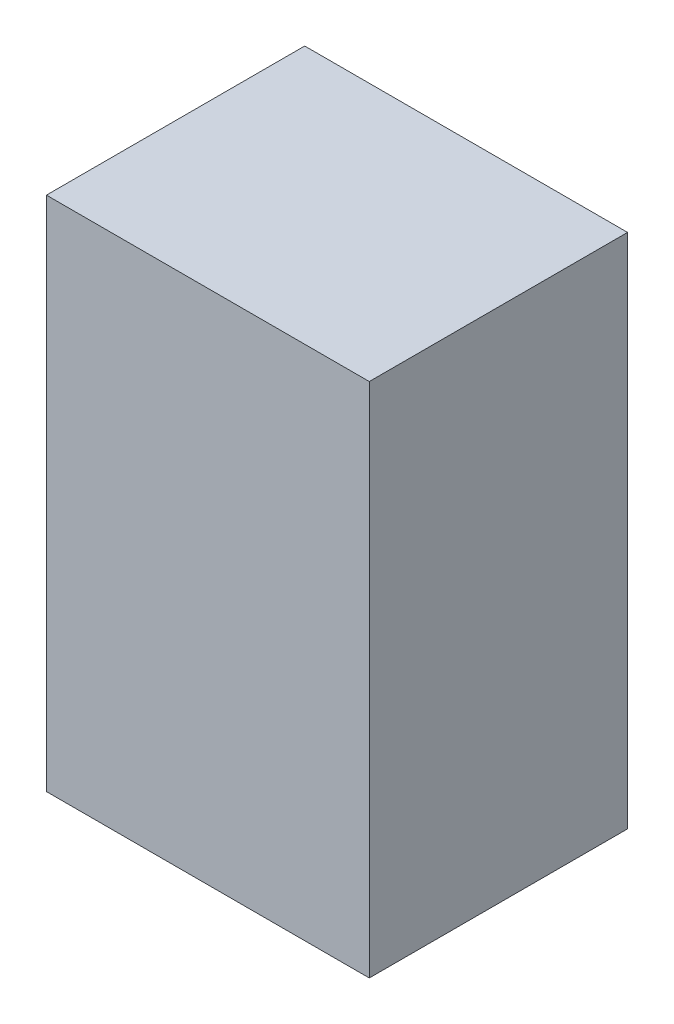
SolidWorks part; units mm, degrees
ref_plane "Front Plane" through (0, 0, 0) normal (0, 0, 1) x (1, 0, 0)
ref_plane "Top Plane" through (0, 0, 0) normal (0, 1, 0) x (1, 0, 0)
ref_plane "Right Plane" through (0, 0, 0) normal (1, 0, 0) x (0, 0, -1)
sketch "Sketch1" plane through (0, 0, 0) normal (0, 0, 1) x (1, 0, 0)
  line L1 (0, 0) -> (0.25, 0)
  line L2 (0, 0) -> (0, 0.4)
  line L3 (0, 0.4) -> (0.25, 0.4)
  line L4 (0.25, 0) -> (0.25, 0.4)
  dimension "D1" = 0.25
  dimension "D2" = 0.4
extrude "Boss-Extrude1" add sketch "Sketch1" along normal blind 0.2 contours L2 L3 L4 L1
equation "\"t\"= 0.25'thickness of the sheets"
equation "\"t_cf\" = 0.115'thickness of single carbon fiber layer"
equation "\"t_kapton\" = 0.025'thickness of single Kapton flex layer"
equation "\"t_fr4\" = 0.1'thickness of FR4 with copper layer"
equation "\"joint_flex\"= 0.1'Width of flextures gap"
equation "\"joint_flex_eff\"= 0.02'Width of flecture after castelation"
equation "\"joint_fold\"= 0.2'Width of folding joints for 90deg fold"
equation "\"gap_tolerance\"= 0.002'Width to have interfecence fit between carbon fiber inserts"
equation "\"assemble_angle\"= 90'Angle of assembly parts"
equation "\"link_lift\"= 0.5'Actuation linkage amplification for the lift motion"
equation "\"link_swing\"= 0.45'Actuation linkage amplification for the swing motion"
equation "\"D1@Sketch1\"=\"t\""
equation "\"D1@Boss-Extrude1\"=\"joint_fold\""
